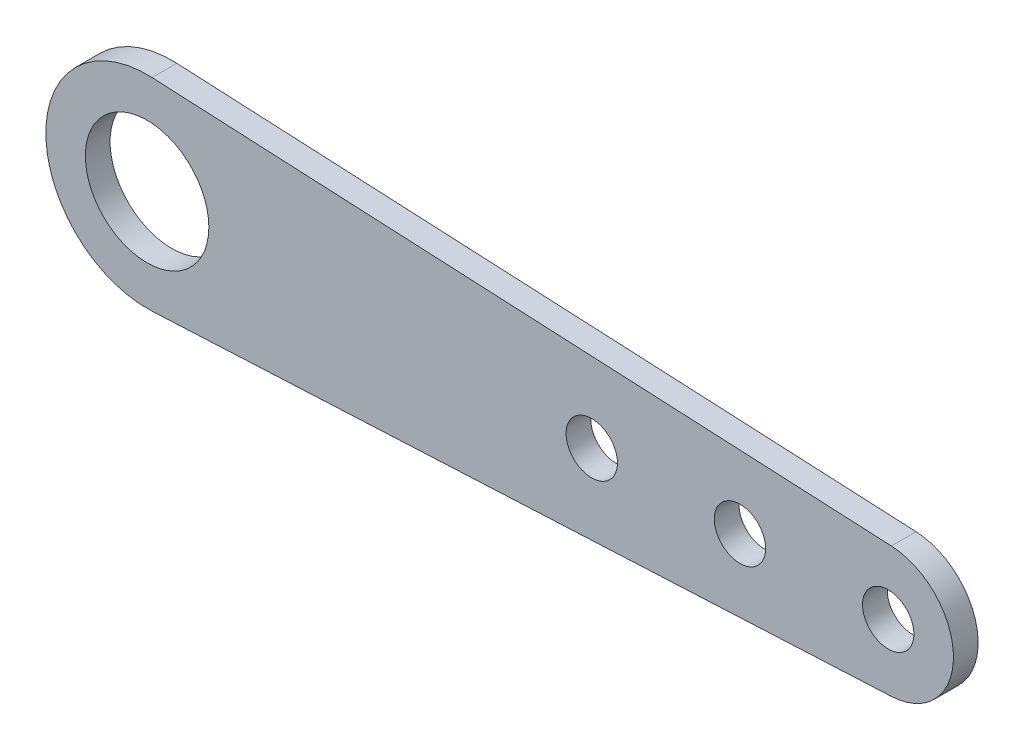
SolidWorks part; units mm, degrees
material "AISI 4130 Steel, annealed at 865C"
ref_plane "Front Plane" through (0, 0, 0) normal (0, 0, 1) x (1, 0, 0)
ref_plane "Top Plane" through (0, 0, 0) normal (0, 1, 0) x (1, 0, 0)
ref_plane "Right Plane" through (0, 0, 0) normal (1, 0, 0) x (0, 0, -1)
sketch "Sketch1" plane through (0, 0, 0) normal (0, 0, 1) x (1, 0, 0)
  line L0 (0, 0) -> (57.15, 0) construction
  line L1 (57.15, 0) -> (76.2, 0) construction
  line L2 (0.6335, 13.0021) -> (95.6579, 8.3721)
  line L3 (0.6335, -13.0021) -> (95.6579, -8.3721)
  arc A0 (0.6335, 13.0021) -> (0.6335, -13.0021) centre (0, 0) ccw
  circle A1 centre (0, 0) radius 7.9375
  circle A2 centre (57.15, 0) radius 3.302
  circle A3 centre (76.2, 0) radius 3.302
  circle A4 centre (95.25, 0) radius 3.302
  arc A5 (95.6579, -8.3721) -> (95.6579, 8.3721) centre (95.25, 0) ccw
  point P17 (122.2546, 12.32)
  dimension "D1" = 15.875
  dimension "D2" = 5.08
  dimension "D3" = 6.604
  dimension "D7" = 5.08
  dimension "D4" = 76.2
  dimension "D6" = 19.05
  dimension "D5" = 3
extrude "Boss-Extrude1" add sketch "Sketch1" along normal blind 3.175
